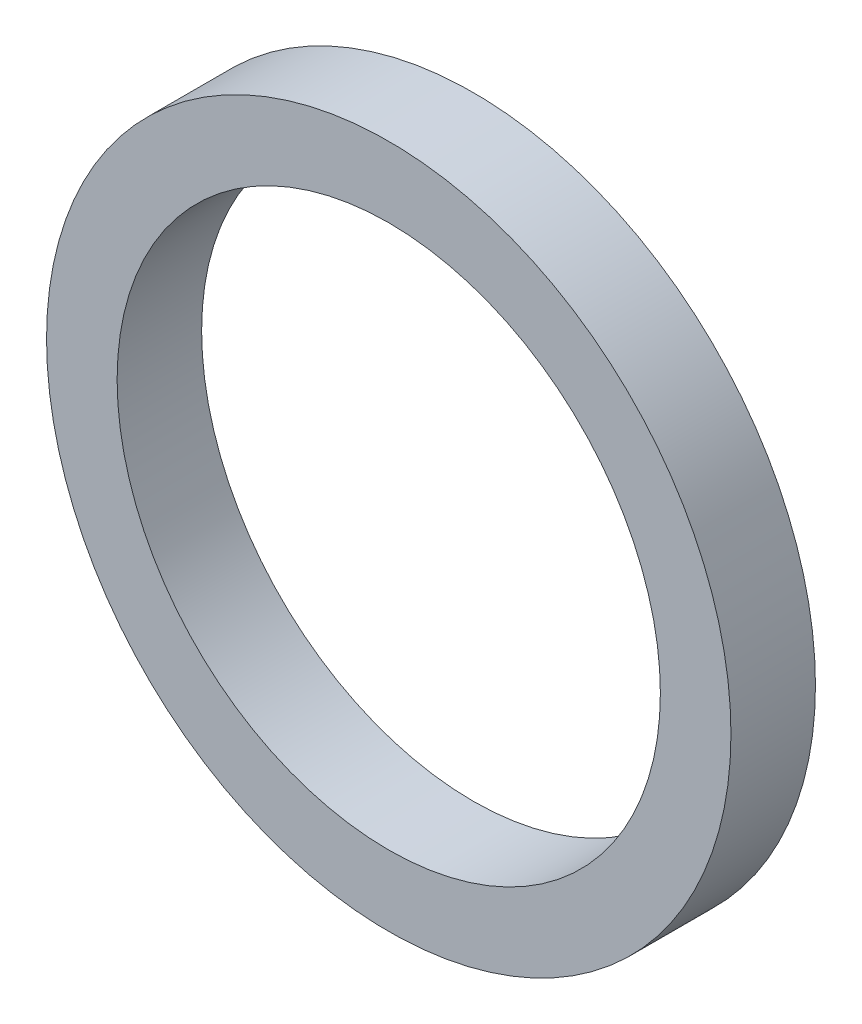
SolidWorks part; units mm, degrees
material "6061 Alloy"
ref_plane "Front Plane" through (0, 0, 0) normal (0, 0, 1) x (1, 0, 0)
ref_plane "Top Plane" through (0, 0, 0) normal (0, 1, 0) x (1, 0, 0)
ref_plane "Right Plane" through (0, 0, 0) normal (1, 0, 0) x (0, 0, -1)
sketch "Sketch1" plane through (0, 0, 0) normal (0, 0, 1) x (1, 0, 0)
  circle A0 centre (0, 0) radius 36
  circle A1 centre (0, 0) radius 28.575
  dimension "D1" = 72
  dimension "D2" = 57.15
extrude "Boss-Extrude1" add sketch "Sketch1" along normal blind 8.89
